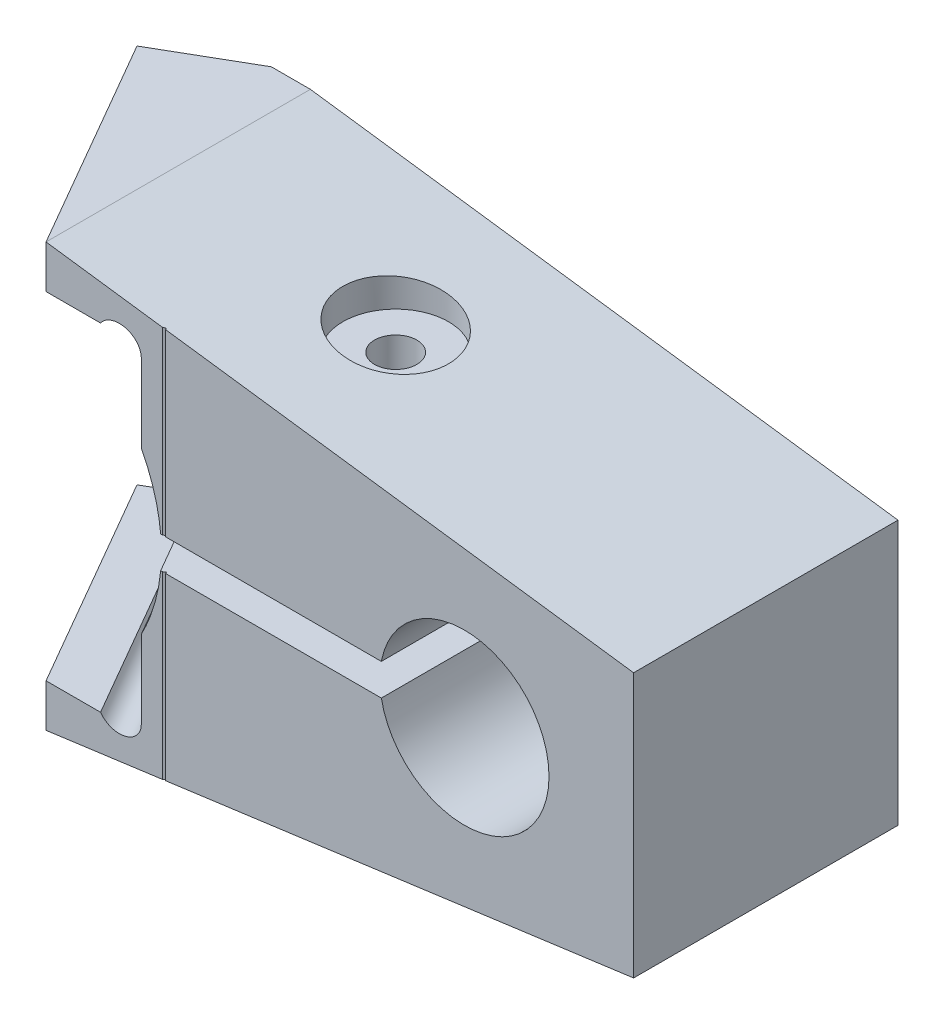
SolidWorks part; units mm, degrees
material "ABS"
ref_plane "Front Plane" through (0, 0, 0) normal (0, 0, 1) x (1, 0, 0)
ref_plane "Top Plane" through (0, 0, 0) normal (0, 1, 0) x (1, 0, 0)
ref_plane "Right Plane" through (0, 0, 0) normal (1, 0, 0) x (0, 0, -1)
sketch "Sketch1" plane through (0, 0, 0) normal (0, 1, 0) x (1, 0, 0)
  line L0 (-35, 12.5) -> (-20.5662, -12.5)
  line L1 (-20.5662, -12.5) -> (35, -12.5)
  line L2 (-27.7831, 0) -> (-41.077, -7.6752) construction
  line L3 (-35, 12.5) -> (35, 12.5)
  line L4 (35, -12.5) -> (35, 12.5)
  line L5 (-23.0337, -8.2263) -> (35, 12.5) construction
  line L6 (-35, 12.5) -> (35, -12.5) construction
  point P0 (0, 0)
  dimension "D1" = 70
  dimension "D2" = 25
  dimension "D3" = 120
extrude "Boss-Extrude1" add sketch "Sketch1" along normal blind 40
sketch "Sketch2" plane through (0, 0, 12.5) normal (0, 0, 1) x (1, 0, 0)
  line L0 (-20.5662, 40) -> (35, 32.5)
  line L1 (35, 40) -> (35, 0) construction
  line L3 (35, 7.5) -> (-20.5662, 0)
  line L4 (-20.5662, 0) -> (35, 0)
  line L5 (35, 0) -> (35, 7.5)
  line L6 (35, 32.5) -> (35, 40)
  line L7 (35, 40) -> (-20.5662, 40)
  dimension "D1" = 25
  dimension "D2" = 7.5
  dimension "D3" = 7.5
  dimension "D4" = 97.687
  dimension "D5" = 97.687
extrude "Cut-Extrude1" cut sketch "Sketch2" against normal blind 40
sketch "Sketch3" plane through (-20.8373, 0, 12.0304) normal (-0.866, 0, 0.5) x (0.5, 0, 0.866)
  line L1 (-12.8642, 25.3819) -> (-8.4874, 25.3819)
  line L2 (-12.8642, 25.3819) -> (-12.8642, 17.4606)
  line L3 (-12.8642, 17.4606) -> (-8.4874, 17.4606)
  line L4 (-8.4874, 25.3819) -> (-8.4874, 17.4606)
  line L5 (-12.8642, 25.3819) -> (-8.4874, 17.4606) construction
  line L6 (-12.8642, 17.4606) -> (-8.4874, 25.3819) construction
  point P0 (-10.6758, 21.4213)
extrude "Boss-Extrude2" add sketch "Sketch3" along normal blind 40
sketch "Sketch4" plane through (-4.2437, 0, -7.3503) normal (0.5, 0, 0.866) x (0.866, 0, -0.5)
  line L0 (-25.2609, 35.9341) -> (-19.5976, 35.9341)
  line L1 (-52.0609, 0.9968) -> (-14.0609, 0.9968) construction
  line L2 (-52.0609, 0.9968) -> (-52.0609, 38.9968) construction
  line L3 (-52.0609, 38.9968) -> (-14.0609, 38.9968) construction
  line L4 (-14.0609, 0.9968) -> (-14.0609, 38.9968) construction
  line L5 (-52.0609, 0.9968) -> (-20.0148, 33.0429) construction
  line L6 (-52.0609, 38.9968) -> (-14.0609, 0.9968) construction
  line L7 (-24.0609, 40) -> (-24.0609, 0) construction
  line L8 (-16.2609, 34.9968) -> (-16.2609, 27.6232)
  line L9 (-16.7881, 36.2696) -> (-14.0609, 38.9968) construction
  line L10 (-69.3542, 19.9968) -> (-7.4274, 19.9968) construction
  line L11 (-16.2609, 4.9968) -> (-16.2609, 12.3703)
  line L12 (-25.2609, 4.0594) -> (-19.5976, 4.0594)
  line L13 (-25.2609, 35.9341) -> (-25.2609, 26.6131)
  line L14 (-25.2609, 26.6131) -> (-69.3542, 27.5468)
  line L15 (-69.3542, 27.5468) -> (-69.3542, 11.5496)
  line L16 (-69.3542, 11.5496) -> (-25.2609, 11.5496)
  line L17 (-25.2609, 11.5496) -> (-25.2609, 4.0594)
  arc A0 (-16.2609, 34.9968) -> (-19.5976, 35.9341) centre (-18.0609, 34.9968) ccw
  arc A1 (-16.2609, 4.9968) -> (-19.5976, 4.0594) centre (-18.0609, 4.9968) cw
  arc A2 (-16.2609, 12.3703) -> (-16.2609, 27.6232) centre (-33.0609, 19.9968) ccw
  point P0 (-33.0609, 19.9968)
  dimension "D4" = 3.6
  dimension "D5" = 5.6633
  dimension "D8" = 36.9
  dimension "D1" = 38
  dimension "D2" = 38
  dimension "D3" = 10
  dimension "D6" = 4
  dimension "D7" = 9
extrude "Cut-Extrude2" cut sketch "Sketch4" against normal through all both and the other way through all
sketch "Sketch5" plane through (0, 0, -12.5) normal (0, 0, -1) x (-1, 0, 0)
  line L0 (-35, 32.5) -> (-35, 7.5) construction
  line L1 (35, 40) -> (20.5662, 40) construction
  line L2 (-11.1413, 21.5) -> (29.8749, 21.5)
  line L3 (29.8749, 21.5) -> (29.8749, 18.5)
  line L4 (29.8749, 18.5) -> (-11.1425, 18.5)
  arc A0 (-11.1413, 21.5) -> (-11.1425, 18.5) centre (-19, 20.0032) ccw
  point P1 (-35, 20)
  dimension "D1" = 16
  dimension "D2" = 16
  dimension "D3" = 3
  dimension "D4" = 1.5
  dimension "D5" = 18.5
  dimension "D6" = 18.5
extrude "Cut-Extrude3" cut sketch "Sketch5" against normal blind 40
sketch "Sketch6" plane through (0, 18.5, 0) normal (0, 1, 0) x (1, 0, 0)
  circle A0 centre (0, 0) radius 2
  dimension "D1" = 4
extrude "Cut-Extrude4" cut sketch "Sketch6" against normal through all both and the other way through all
sketch "Sketch7" plane through (0, 0, 0) normal (0, -1, 0) x (1, 0, 0)
  line L1 (1.8526, 3.4614) -> (-2.0714, 3.3351)
  line L2 (-2.0714, 3.3351) -> (-3.9239, -0.1263)
  line L3 (-3.9239, -0.1263) -> (-1.8526, -3.4614)
  line L4 (-1.8526, -3.4614) -> (2.0714, -3.3351)
  line L5 (2.0714, -3.3351) -> (3.9239, 0.1263)
  line L6 (3.9239, 0.1263) -> (1.8526, 3.4614)
  circle A0 centre (0, 0) radius 3.4 construction
  dimension "D1" = 6.8
extrude "Cut-Extrude5" cut sketch "Sketch7" against normal blind 5
sketch "Sketch8" plane through (0, 40, 0) normal (0, 1, 0) x (1, 0, 0)
  circle A0 centre (0, 0) radius 5
  dimension "D1" = 10
extrude "Cut-Extrude6" cut sketch "Sketch8" against normal blind 5
sketch "Sketch9" plane through (-14.0823, 0, 8.1304) normal (-0.866, 0, 0.5) x (0.5, 0, 0.866)
  line L0 (-28.3253, 40) -> (0.5422, 40) construction
  line L1 (6.0455, 1) -> (-22.9545, 1) construction
  line L2 (6.0455, 1) -> (6.0455, 39) construction
  line L3 (6.0455, 39) -> (-22.9545, 39) construction
  line L4 (-22.9545, 1) -> (-22.9545, 39) construction
  line L5 (6.0455, 1) -> (-22.9545, 39) construction
  line L6 (6.0455, 39) -> (-22.9545, 1) construction
  line L7 (5.0455, 34.9968) -> (5.0455, 27.6232) construction
  line L8 (-22.9545, 45.7496) -> (-22.9545, -7.6537)
  line L9 (-22.9545, -7.6537) -> (-29.1772, -7.6537)
  line L10 (-29.1772, -7.6537) -> (-29.1772, 45.7496)
  line L11 (-29.1772, 45.7496) -> (-22.9545, 45.7496)
  line L12 (6.0455, 45.7496) -> (6.0455, -7.6537)
  line L13 (6.0455, -7.6537) -> (13.7172, -7.6537)
  line L14 (13.7172, -7.6537) -> (13.7172, 42.6866)
  line L15 (13.7172, 42.6866) -> (13.7172, 45.7496)
  line L16 (13.7172, 45.7496) -> (6.0455, 45.7496)
  point P0 (-8.4545, 20)
  dimension "D1" = 38
  dimension "D2" = 1
  dimension "D3" = 29
  dimension "D4" = 1
extrude "Cut-Extrude7" cut sketch "Sketch9" along direction (0.866, 0, -0.5) on the side of the normal blind 16 from offset 2
